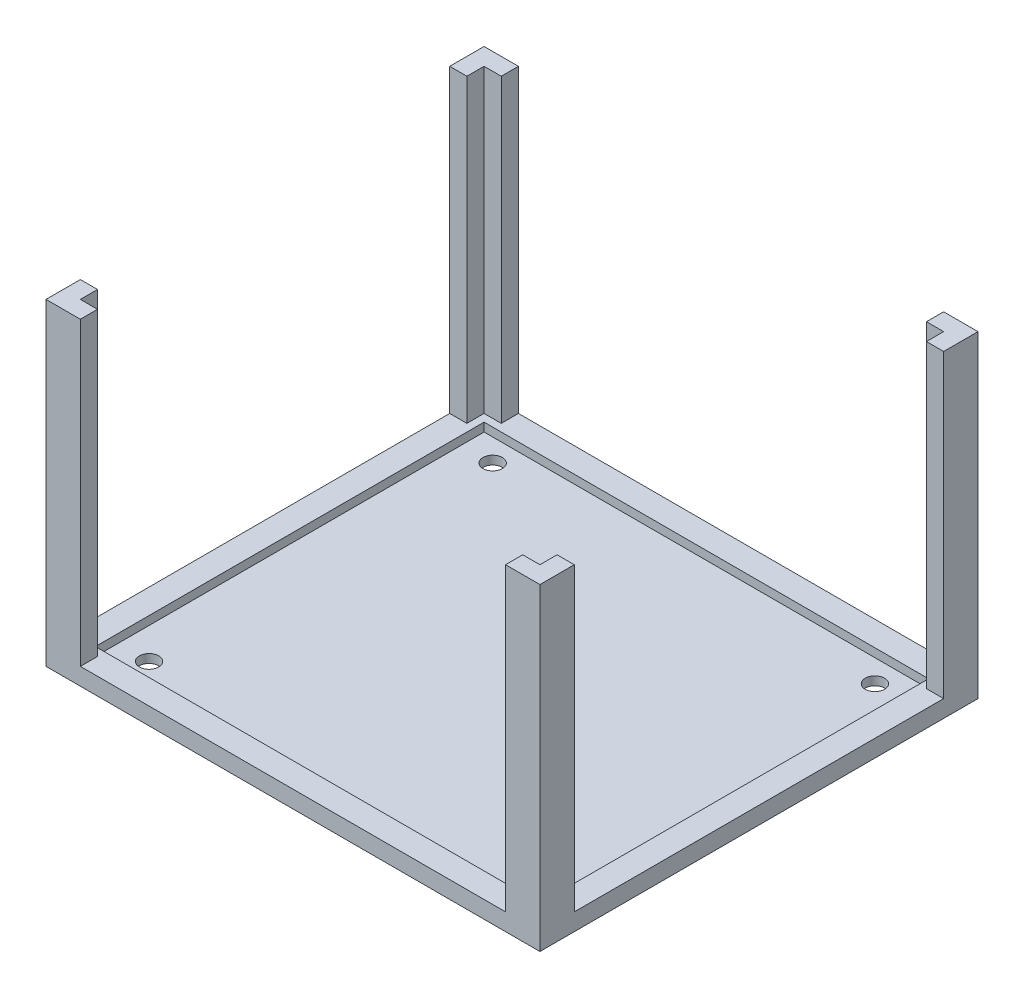
SolidWorks part; units mm, degrees
ref_plane "Front Plane" through (0, 0, 0) normal (0, 0, 1) x (1, 0, 0)
ref_plane "Top Plane" through (0, 0, 0) normal (0, 1, 0) x (1, 0, 0)
ref_plane "Right Plane" through (0, 0, 0) normal (1, 0, 0) x (0, 0, -1)
sketch "Sketch1" plane through (0, 0, 0) normal (0, 1, 0) x (1, 0, 0)
  line L1 (0, 0) -> (115, 0)
  line L2 (0, 0) -> (0, 102)
  line L3 (0, 102) -> (115, 102)
  line L4 (115, 0) -> (115, 102)
  dimension "D1" = 115
  dimension "D2" = 102
extrude "Boss-Extrude1" add sketch "Sketch1" along normal blind 4
sketch "Sketch3" plane through (0, 0, 0) normal (0, -1, 0) x (1, 0, 0)
  line L0 (115, -102) -> (0, -102) construction
  line L1 (5.5, -6) -> (20.5, -6)
  line L2 (5.5, -6) -> (5.5, -96)
  line L3 (5.5, -96) -> (20.5, -96)
  line L4 (20.5, -6) -> (20.5, -96)
  line L5 (57.5, 0) -> (57.5, -102) construction
  line L6 (0, 0) -> (115, 0) construction
  line L7 (0, -51) -> (115, -51) construction
  line L8 (109.5, -6) -> (94.5, -6)
  line L9 (109.5, -6) -> (109.5, -96)
  line L10 (109.5, -96) -> (94.5, -96)
  line L11 (94.5, -6) -> (94.5, -96)
  line L14 (0, -102) -> (0, 0) construction
  line L17 (115, 0) -> (115, -102) construction
  dimension "D1" = 104
  dimension "D2" = 90
  dimension "D3" = 15
  dimension "D4" = 90
sketch "Sketch11" plane through (0, 4, 0) normal (0, 1, 0) x (1, 0, 0)
  line L5 (5.75, 96.25) -> (109.25, 96.25)
  line L6 (5.75, 96.25) -> (5.75, 5.75)
  line L7 (5.75, 5.75) -> (109.25, 5.75)
  line L8 (109.25, 96.25) -> (109.25, 5.75)
  line L10 (115, 102) -> (0, 102) construction
  line L11 (115, 0) -> (115, 102) construction
  point P6 (57.5, 102)
  point P7 (57.5, 96.25)
  point P10 (115, 51)
  point P11 (109.25, 51)
  dimension "D1" = 103.5
  dimension "D2" = 90.5
extrude "Cut-Extrude5" cut sketch "Sketch11" against normal blind 2
sketch "Sketch16" plane through (0, 2, 0) normal (0, 1, 0) x (1, 0, 0)
  line L0 (5.5, 6) -> (5.5, 96) construction
  line L1 (0, 51) -> (115, 51) construction
  line L2 (0, 102) -> (0, 0) construction
  line L5 (57.5, 0) -> (57.5, 102) construction
  line L6 (0, 0) -> (115, 0) construction
  line L7 (115, 0) -> (115, 102) construction
  circle A0 centre (13, 11) radius 2.25
  circle A1 centre (13, 91) radius 2.25
  circle A2 centre (102, 91) radius 2.25
  circle A3 centre (102, 11) radius 2.25
  point P21 (0, 0)
  dimension "D1" = 4.5
  dimension "D2" = 7.5
  dimension "D3" = 80
extrude "Cut-Extrude7" cut sketch "Sketch16" against normal blind 13
sketch "Sketch6" plane through (0, 4, 0) normal (0, 1, 0) x (1, 0, 0)
  line L0 (0, 0) -> (0, 8)
  line L1 (0, 102) -> (0, 0) construction
  line L2 (0, 8) -> (4, 8)
  line L3 (4, 8) -> (4, 4)
  line L4 (4, 4) -> (8, 4)
  line L5 (8, 4) -> (8, 0)
  line L6 (0, 0) -> (115, 0) construction
  line L7 (8, 0) -> (0, 0)
  line L8 (57.5, 0) -> (57.5, 102) construction
  line L9 (115, 102) -> (0, 102) construction
  line L10 (0, 51) -> (115, 51) construction
  line L11 (115, 0) -> (115, 102) construction
  line L12 (107, 0) -> (115, 0)
  line L13 (107, 4) -> (107, 0)
  line L14 (111, 4) -> (107, 4)
  line L15 (111, 8) -> (111, 4)
  line L16 (115, 8) -> (111, 8)
  line L17 (115, 0) -> (115, 8)
  line L18 (107, 102) -> (115, 102)
  line L19 (115, 102) -> (115, 94)
  line L20 (115, 94) -> (111, 94)
  line L21 (111, 94) -> (111, 98)
  line L22 (111, 98) -> (107, 98)
  line L23 (107, 98) -> (107, 102)
  line L24 (8, 102) -> (0, 102)
  line L25 (8, 98) -> (8, 102)
  line L26 (4, 98) -> (8, 98)
  line L27 (4, 94) -> (4, 98)
  line L28 (0, 94) -> (4, 94)
  line L29 (0, 102) -> (0, 94)
  dimension "D1" = 4
  dimension "D2" = 4
  dimension "D3" = 8
  dimension "D4" = 8
extrude "Boss-Extrude4" add sketch "Sketch6" along normal blind 70
